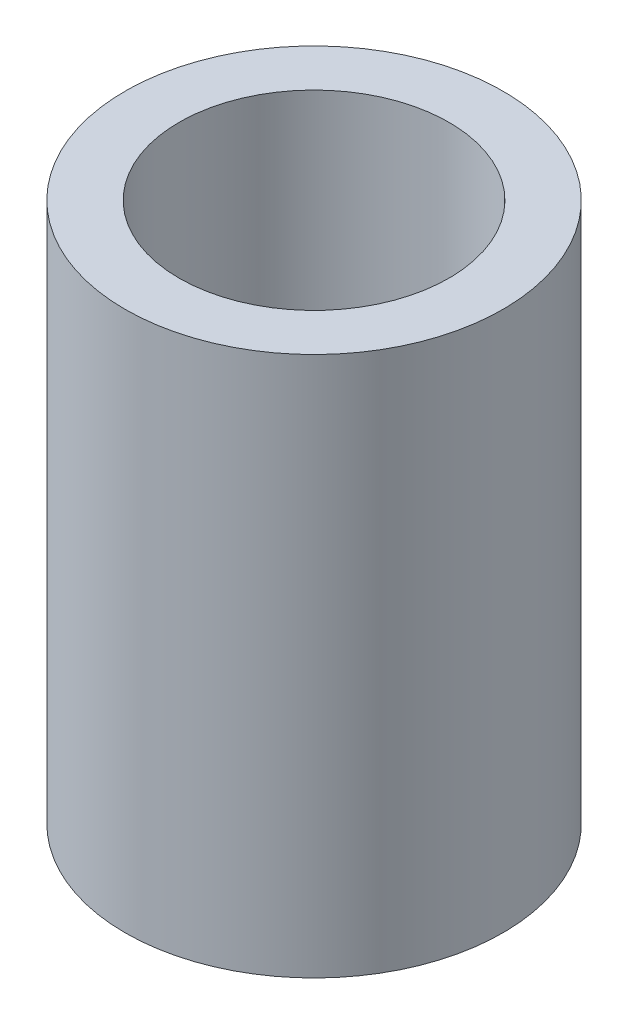
SolidWorks part; units mm, degrees
material "黄铜"
ref_plane "前视基准面" through (0, 0, 0) normal (0, 0, 1) x (1, 0, 0)
ref_plane "上视基准面" through (0, 0, 0) normal (0, 1, 0) x (1, 0, 0)
ref_plane "右视基准面" through (0, 0, 0) normal (1, 0, 0) x (0, 0, -1)
other "Configuration Table"
sketch "草图1" plane through (0, 0, 0) normal (0, 1, 0) x (1, 0, 0)
  circle A0 centre (0, 0) radius 2.1
  circle A1 centre (0, 0) radius 1.5
  dimension "D1" = 4.2
  dimension "D2" = 3
extrude "凸台-拉伸1" add sketch "草图1" along normal mid plane 6
